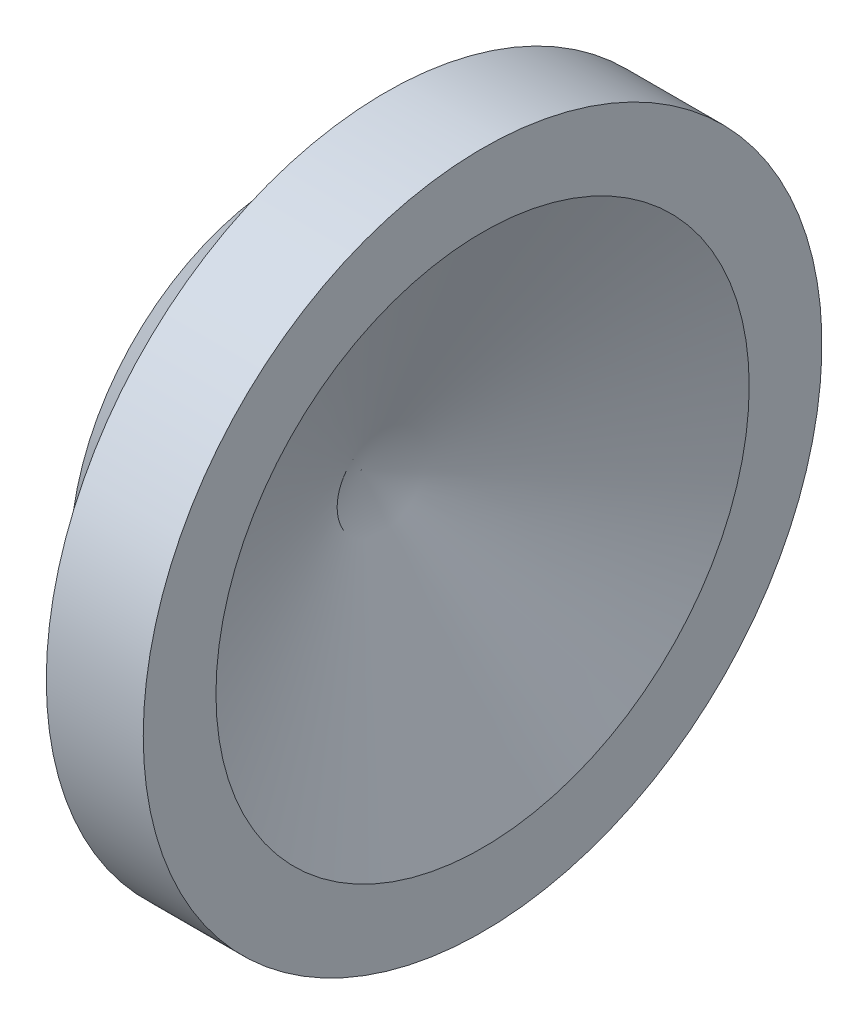
SolidWorks part; units mm, degrees
ref_plane "Front Plane" through (0, 0, 0) normal (0, 0, 1) x (1, 0, 0)
ref_plane "Top Plane" through (0, 0, 0) normal (0, 1, 0) x (1, 0, 0)
ref_plane "Right Plane" through (0, 0, 0) normal (1, 0, 0) x (0, 0, -1)
sketch "Sketch1" plane through (0, 0, 0) normal (0, 1, 0) x (1, 0, 0)
  line L0 (0, 0) -> (-0.75, 0)
  line L1 (-0.75, 0) -> (-1, -0.25)
  line L2 (-1, -0.25) -> (-1, 2)
  line L3 (-1, 2) -> (-0.25, 2)
  line L4 (-0.25, 2) -> (1, -0.75)
  line L5 (1, -0.75) -> (1, -1.5)
  line L6 (1, -1.5) -> (0, -1.5)
  line L7 (0, -1.5) -> (0, 0)
  dimension "D1" = 1
  dimension "D2" = 1
  dimension "D3" = 45
  dimension "D4" = 2
  dimension "D5" = 0.75
  dimension "D6" = 0.25
  dimension "D7" = 0.75
  dimension "D8" = 3.5
revolve "Revolve1" add sketch "Sketch1" angle 360 about L3
